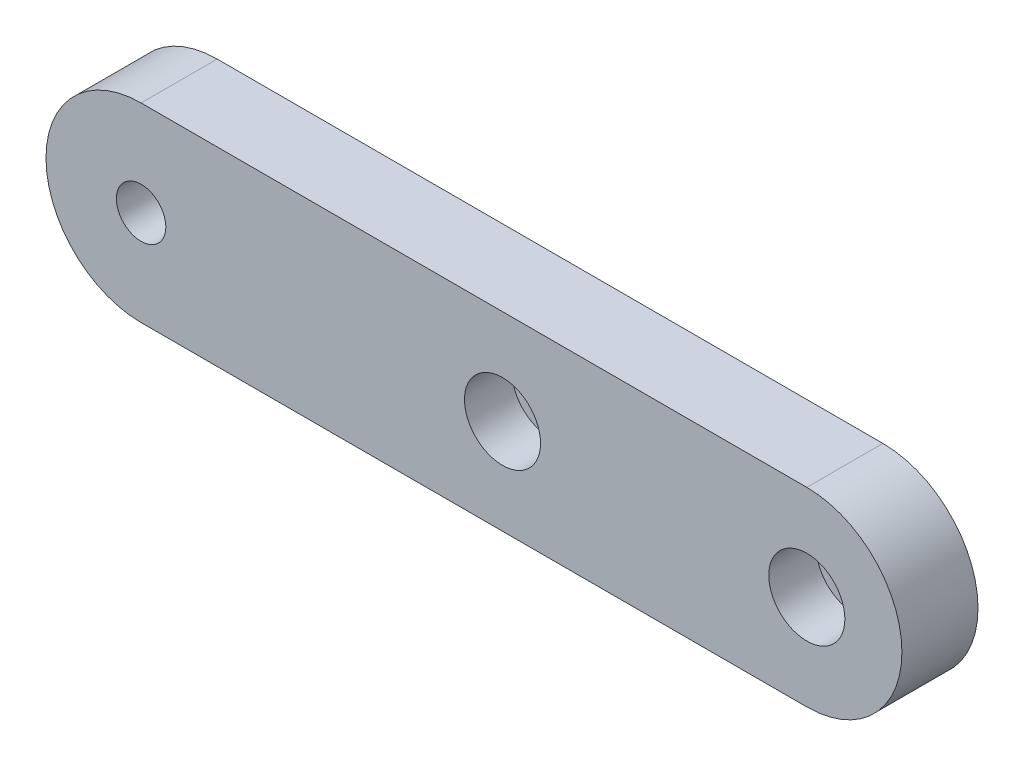
SolidWorks part; units mm, degrees
ref_plane "Plan de face" through (0, 0, 0) normal (0, 0, 1) x (1, 0, 0)
ref_plane "Plan de dessus" through (0, 0, 0) normal (0, 1, 0) x (1, 0, 0)
ref_plane "Plan de droite" through (0, 0, 0) normal (1, 0, 0) x (0, 0, -1)
sketch "Esquisse1" plane through (0, 0, 0) normal (0, 0, 1) x (1, 0, 0)
  line L1 (-17.5, -5) -> (17.5, -5)
  line L2 (-17.5, -5) -> (-17.5, 5)
  line L3 (-17.5, 5) -> (17.5, 5)
  line L4 (17.5, -5) -> (17.5, 5)
  line L5 (-17.5, -5) -> (17.5, 5) construction
  line L6 (-17.5, 5) -> (17.5, -5) construction
  arc A0 (-17.5, -5) -> (-17.5, 5) centre (-17.5, 0) cw
  arc A1 (17.5, 5) -> (17.5, -5) centre (17.5, 0) cw
  point P0 (0, 0)
  dimension "D1" = 10
  dimension "D2" = 35
extrude "Boss.-Extru.1" add sketch "Esquisse1" along normal blind 4 contours L1 L4 L3 L2 | A1 L4 | A0 L2
sketch "Esquisse2" plane through (0, 0, 4) normal (0, 0, 1) x (1, 0, 0)
  circle A0 centre (17.5, 0) radius 1.1913
  circle A1 centre (1.5005, 0) radius 1.1913
  circle A2 centre (-17.5, 0) radius 1.3
  dimension "D1" = 2.3825
  dimension "D3" = 2.6
  dimension "D2" = 15.9995
extrude "Enlèv. mat.-Extru.1" cut sketch "Esquisse2" against normal up to next
sketch "Esquisse3" plane through (0, 0, 4) normal (0, 0, 1) x (1, 0, 0)
  line L0 (1.5005, 0) -> (17.5, 0) construction
  circle A1 centre (9.5003, 0) radius 0.5
  point P4 (9.5003, 0)
  dimension "D1" = 1
sketch "Esquisse4" plane through (0, 0, 4) normal (0, 0, 1) x (1, 0, 0)
  circle A0 centre (17.5, 0) radius 2
  circle A1 centre (1.5005, 0) radius 2
  dimension "D1" = 4
extrude "Enlèv. mat.-Extru.2" cut sketch "Esquisse4" against normal offset from surface (2.5 mm away) 1.5 up to face at (18.6913, 0, 0)
